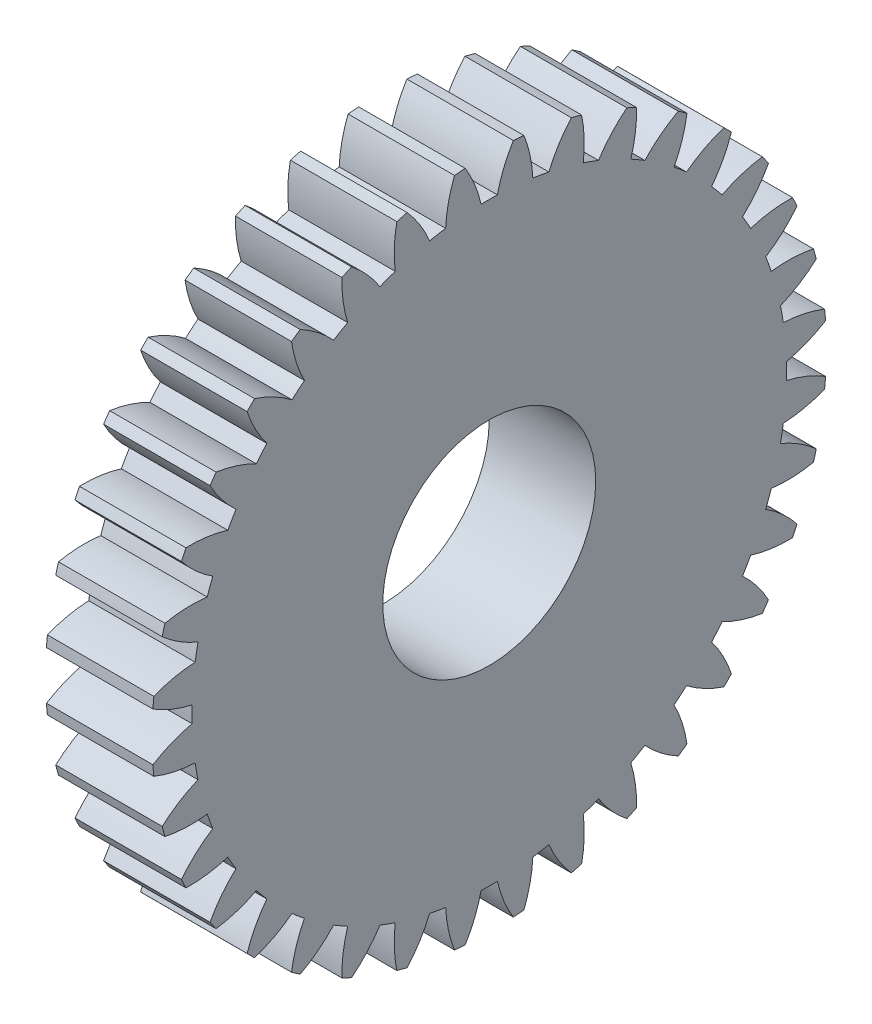
SolidWorks part; units mm, degrees
ref_plane "Plane1" through (0, 0, 0) normal (0, 0, 1) x (1, 0, 0)
ref_plane "Plane2" through (0, 0, 0) normal (0, 1, 0) x (1, 0, 0)
ref_plane "Plane3" through (0, 0, 0) normal (1, 0, 0) x (0, 0, -1)
other "Configuration Table"
sketch "HoldingSke" plane through (0, 0, 0) normal (0, 1, 0) x (1, 0, 0)
  line L0 (0, 0) -> (493.1768, -358.3139)
  line L1 (-15, 0) -> (100, 0) construction
  line L2 (0, 0) -> (-2.1039, 2.3779)
  line L3 (0, 0) -> (-11.863, 4.5341)
  line L4 (0, 0) -> (6.9867, 5.0761)
  line L5 (0, 0) -> (-47.5972, -17.7524)
  line L6 (0, 0) -> (-5.2639, -3.5516)
  line L7 (-2.1039, 2.3779) -> (8.8308, 51.9871)
  line L8 (-76.2, 54.61) -> (-54.9402, 54.61)
  line L9 (-71.009, 38.7566) -> (-53.1078, 45.2721)
  line L10 (-76.2, 71.12) -> (104.1128, 71.12)
  line L11 (0, 0) -> (-6.35, 0)
  line L12 (-76.2, 101.6) -> (-76.1573, 101.6)
  line L13 (24.9733, 27.94) -> (52.9518, 28.4284)
  line L14 (24.9733, 27.94) -> (25.0241, 27.9398)
  line L15 (24.9733, 27.94) -> (100.4021, 29.52)
  circle A0 centre (0, 0) radius 9.525
  circle A1 centre (0, 0) radius 17.7292
  circle A2 centre (0, 0) radius 38.1
  circle A3 centre (0, 0) radius 9.525
  dimension "MHD" = 35.4584
  dimension "Hub_dia" = 76.2
  dimension "Bore" = 19.05
  dimension "MBD" = 19.05
  dimension "Num_teeth" = 36
  dimension "Pitch" = 609.6
  dimension "Overall_len" = 50.8
  dimension "Show_teeth" = 36
  dimension "Thickness" = 6.35
  dimension "OAL" = 50.8001
  dimension "T_dim" = 21.2598
  dimension "Ap" = 20
  dimension "H" = 19.05
  dimension "Pitch_radius" = 180.3128
  dimension "Width" = 6.35
  dimension "Backlash" = 0.0427
  dimension "Addendum_fac" = 1
  dimension "Dedendum_fac" = 1.2
  dimension "Clearance_fac" = 0.2
  dimension "Dedendum_add" = 0.0508
sketch "BasProSke" plane through (0, 0, 0) normal (0, 1, 0) x (1, 0, 0)
  line L0 (-10, 0) -> (60, 0) construction
  line L1 (0, 0) -> (0, 20.1083)
  line L2 (0, 0) -> (6.35, 0)
  line L3 (6.35, 0) -> (6.35, 20.1083)
  line L4 (6.35, 20.1083) -> (0, 20.1083)
  dimension "Thickness" = 6.35
  dimension "Diameter" = 40.2167
revolve "Base-Revolve" add sketch "BasProSke" angle 360 about L0
sketch "TooCutSke" plane through (0, 0, 0) normal (1, 0, 0) x (0, 0, -1)
  line L1 (0, 0) -> (0, 107) construction
  line L2 (0, 0) -> (-0.9056, 19.0285) construction
  line L3 (0, 0) -> (-3.318, 37.9251) construction
  line L4 (-0.9056, 19.0285) -> (-1.659, 18.9625) construction
  arc A0 (0.4859, 17.7225) -> (-0.4859, 17.7225) centre (0, 0) ccw
  arc A1 (1.4524, 20.0813) -> (-1.4524, 20.0813) centre (0, 0) ccw
  circle A2 centre (0, 0) radius 19.05 construction
  circle A3 centre (0, 0) radius 17.9011 construction
  arc A4 (-0.4859, 17.7225) -> (-1.4524, 20.0813) centre (-7.9208, 16.0534) ccw
  arc A5 (1.4524, 20.0813) -> (0.4859, 17.7225) centre (7.9208, 16.0534) ccw
  dimension "Root_dia" = 35.4584
  dimension "Overcut_dia" = 40.2675
  dimension "Pitch_dia" = 38.1
  dimension "Base_dia" = 35.8023
  dimension "Flank_rad" = 7.62
  dimension "Half_ang" = 5
  dimension "Half_CT" = 0.7563
extrude "ToothCut" cut sketch "TooCutSke" along normal through all
fillet "Breaks" [suppressed] radius 0.0212
fillet "RootFillets" [suppressed] radius 0.2625
pattern_circular "TeethCuts" count 36 every 10 about axis through (-10, 0, 0) along (1, 0, 0) of "ToothCut", "RootFillets", "Breaks"
sketch "HubNeaOneSke" plane through (0, 0, 0) normal (-1, 0, 0) x (0, 0, 1)
  circle A0 centre (0, 0) radius 17.7292
  dimension "Diameter" = 35.4584
extrude "HubNearOne" [suppressed] add sketch "HubNeaOneSke" along normal blind 44.4501
sketch "HubNeaBotSke" plane through (0, 0, 0) normal (-1, 0, 0) x (0, 0, 1)
  circle A0 centre (0, 0) radius 17.7292
  dimension "Diameter" = 35.4584
extrude "HubNearBoth" [suppressed] add sketch "HubNeaBotSke" along normal blind 22.225
ref_plane "FarPln" through (6.35, 0, 0) normal (1, 0, 0) x (0, 0, -1)
sketch "HubFarSke" plane through (6.35, 0, 0) normal (1, 0, 0) x (0, 0, -1)
  circle A0 centre (0, 0) radius 17.7292
  dimension "Diameter" = 35.4584
extrude "HubFar" [suppressed] add sketch "HubFarSke" along normal blind 22.225
sketch "BorSke" plane through (0, 0, 0) normal (1, 0, 0) x (0, 0, -1)
  circle A0 centre (0, 0) radius 9.525
  dimension "Diameter" = 19.05
extrude "Bore" cut sketch "BorSke" along normal mid plane 101.6001
sketch "KeySke" plane through (0, 0, 0) normal (1, 0, 0) x (0, 0, -1)
  line L0 (-2.3813, 0) -> (-2.3813, 11.7348)
  line L1 (-2.3813, 11.7348) -> (2.3813, 11.7348)
  line L2 (2.3813, 11.7348) -> (2.3813, 0)
  line L3 (0, 0) -> (0, 34) construction
  line L4 (-2.3813, 0) -> (2.3813, 0)
  dimension "Offset" = 11.7348
  dimension "Width" = 4.7625
extrude "Keyway" [suppressed] cut sketch "KeySke" along normal mid plane 101.6001
pattern_circular "Keyway2" [suppressed] count 2 every 90 about axis through (-10, 0, 0) along (1, 0, 0)
sketch "Sketch1" plane through (6.35, 0, 0) normal (1, 0, 0) x (0, 0, -1)
  circle A0 centre (0, 0) radius 9.525
  circle A1 centre (0, 0) radius 6.35
  dimension "D1" = 19.05
  dimension "D2" = 12.7
extrude "Boss-Extrude1" add sketch "Sketch1" against normal up to surface (6.35 mm away) up to face at (0, 0, -9.525)
equation "' \"Pitch@HoldingSke\" = 4"
equation "' \"Num_teeth@HoldingSke\" = 12"
equation "' \"Ap@HoldingSke\" =  20"
equation "' \"Ap@HoldingSke\" = 20"
equation "' \"Width@HoldingSke\" = 0.5"
equation "' \"Hub_dia@HoldingSke\"= 1"
equation "' \"Hub_dia@HoldingSke\" = 1"
equation "' \"Overall_len@HoldingSke\" = 1.0"
equation "' \"Bore@HoldingSke\" = 0.75"
equation "' \"T_dim@HoldingSke\" = 0.85"
equation "' \"Width@KeySke\" = 0.25"
equation "' \"Show_teeth@HoldingSke\" = 13"
equation "' \"Backlash@HoldingSke\" = 0.009"
equation "' \"Addendum_fac@HoldingSke\" = 1.0"
equation "' \"Dedendum_fac@HoldingSke\" = 1.25"
equation "' \"Dedendum_add@HoldingSke\" = 0.00005"
equation "' \"Clearance_fac@HoldingSke\" = 0.25"
equation "' \"Pitch@HoldingSke\" = 0.5"
equation "' \"Num_teeth@HoldingSke\" = 23"
equation "' \"Show_teeth@HoldingSke\" = 23"
equation "' \"Backlash@HoldingSke\" = 0.0375"
equation "\"Overcut_dia@TooCutSke\" = (\"Num_teeth@HoldingSke\" + 2 * \"Addendum_fac@HoldingSke\") / \"Pitch@HoldingSke\" + 0.002"
equation "\"Pitch_dia@TooCutSke\" = \"Num_teeth@HoldingSke\" / \"Pitch@HoldingSke\""
equation "\"Base_dia@TooCutSke\" = \"Num_teeth@HoldingSke\" / \"Pitch@HoldingSke\" * cos((\"Ap@HoldingSke\"  * 3.14159265 / 180))"
equation "\"Root_dia@TooCutSke\" = (\"Num_teeth@HoldingSke\" + 2) / \"Pitch@HoldingSke\" - 2 * (\"Addendum_fac@HoldingSke\" + \"Dedendum_fac@HoldingSke\") / \"Pitch@HoldingSke\" - \"Dedendum_add@HoldingSke\" * 2"
equation "\"Half_ang@TooCutSke\" = 180 / \"Num_teeth@HoldingSke\""
equation "\"Half_CT@TooCutSke\" = \"Num_teeth@HoldingSke\" / \"Pitch@HoldingSke\" * sin((3.14159265 / 2 / \"Num_teeth@HoldingSke\")) / 2 - 7 * \"Backlash@HoldingSke\" / 4"
equation "\"Flank_rad@TooCutSke\" = \"Num_teeth@HoldingSke\" / \"Pitch@HoldingSke\" / 5"
equation "\"Radius@RootFillets\" = \"Clearance_fac@HoldingSke\" / \"Pitch@HoldingSke\" + \"Dedendum_add@HoldingSke\""
equation "\"Break_rad@Breaks\" = 0.02 / \"Pitch@HoldingSke\""
equation "\"Thickness@HoldingSke\" = \"Width@HoldingSke\""
equation "\"OAL@HoldingSke\" = \"Thickness@HoldingSke\""
equation "\"MHD@HoldingSke\" = (\"Num_teeth@HoldingSke\" + 2) / \"Pitch@HoldingSke\" - 2 * (\"Addendum_fac@HoldingSke\" + \"Dedendum_fac@HoldingSke\")  / \"Pitch@HoldingSke\" - \"Dedendum_add@HoldingSke\" * 2"
equation "\"MBD@HoldingSke\" = (\"Num_teeth@HoldingSke\" + 2) / \"Pitch@HoldingSke\" - 2 * (\"Addendum_fac@HoldingSke\" + \"Dedendum_fac@HoldingSke\")  / \"Pitch@HoldingSke\" - \"Dedendum_add@HoldingSke\" * 2 - 0.002"
equation "\"MHD@HoldingSke\" = ((sgn( \"MHD@HoldingSke\" - \"Hub_dia@HoldingSke\" )-1)*( \"MHD@HoldingSke\" - \"Hub_dia@HoldingSke\" ))/-2+ \"Hub_dia@HoldingSke\""
equation "\"MBD@HoldingSke\" = ((sgn( \"MBD@HoldingSke\" - \"Bore@HoldingSke\" )-1)*( \"MBD@HoldingSke\" - \"Bore@HoldingSke\" ))/-2+ \"Bore@HoldingSke\""
equation "\"OAL@HoldingSke\" = ((sgn( \"OAL@HoldingSke\" - \"Overall_len@HoldingSke\" )+1)*( \"OAL@HoldingSke\" - \"Overall_len@HoldingSke\" ))/2 + \"Overall_len@HoldingSke\" + 0.000002"
equation "\"Num_teeth@TeethCuts\" = int( \"Show_teeth@HoldingSke\" ) + 1"
equation "\"Num_teeth@TeethCuts\" = ((sgn( \"Num_teeth@TeethCuts\" - \"Num_teeth@HoldingSke\" )-1)*( \"Num_teeth@TeethCuts\" - \"Num_teeth@HoldingSke\" ))/-2+ \"Num_teeth@HoldingSke\""
equation "\"Num_teeth@TeethCuts\" = ((sgn( \"Num_teeth@TeethCuts\" - 2.0)+1)*( \"Num_teeth@TeethCuts\" - 2.0))/2 +2.0"
equation "\"Angle@TeethCuts\" = 360.0 / \"Num_teeth@HoldingSke\""
equation "\"Diameter@BasProSke\" = (\"Num_teeth@HoldingSke\" + 2 * \"Addendum_fac@HoldingSke\") / \"Pitch@HoldingSke\""
equation "\"Thickness@BasProSke\"  = \"Thickness@HoldingSke\""
equation "' \"Fillet_rad@BasProSke\" =  \"Thickness@HoldingSke\" * 0.05"
equation "' \"Fillet_rad@BasProSke\" = \"Thickness@HoldingSke\" * 0.05"
equation "\"MHD@HoldingSke\" = ((sgn( \"MHD@HoldingSke\" - \"Root_dia@TooCutSke\" )-1)*( \"MHD@HoldingSke\" - \"Root_dia@TooCutSke\" ))/-2+ \"Root_dia@TooCutSke\""
equation "\"Diameter@HubNeaOneSke\" = \"MHD@HoldingSke\""
equation "\"Length@HubNearOne\" = \"OAL@HoldingSke\" - \"Thickness@BasProSke\""
equation "\"Diameter@HubNeaBotSke\" = \"MHD@HoldingSke\""
equation "\"Length@HubNearBoth\" = ( \"OAL@HoldingSke\" - \"Thickness@BasProSke\" ) / 2.0"
equation "\"Thickness@FarPln\" = \"Thickness@BasProSke\""
equation "\"Diameter@HubFarSke\" = \"MHD@HoldingSke\""
equation "\"Length@HubFar\" = ( \"OAL@HoldingSke\" - \"Thickness@BasProSke\" ) / 2.0"
equation "\"Diameter@BorSke\" = \"MBD@HoldingSke\""
equation "\"D1@Bore\" = \"OAL@HoldingSke\" * 2.0"
equation "\"D1@Keyway\" = \"OAL@HoldingSke\" * 2.0"
equation "\"Offset@KeySke\" = \"T_dim@HoldingSke\" - \"MBD@HoldingSke\" / 2.0"
